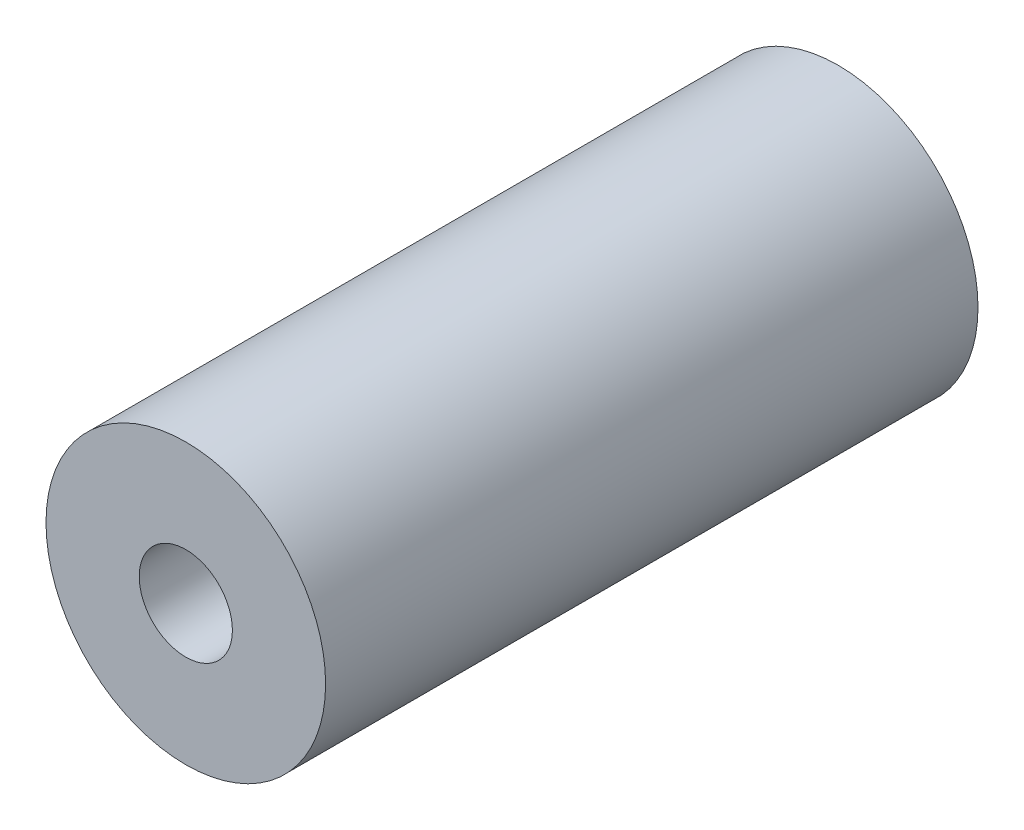
SolidWorks part; units mm, degrees
ref_plane "前视基准面" through (0, 0, 0) normal (0, 0, 1) x (1, 0, 0)
ref_plane "上视基准面" through (0, 0, 0) normal (0, 1, 0) x (1, 0, 0)
ref_plane "右视基准面" through (0, 0, 0) normal (1, 0, 0) x (0, 0, -1)
other "Configuration Table"
sketch "草图1" plane through (0, 0, 0) normal (0, 0, 1) x (1, 0, 0)
  circle A0 centre (0, 0) radius 3
  dimension "D1" = 6
extrude "凸台-拉伸1" add sketch "草图1" along normal blind 14 contours A0
sketch "草图2" plane through (0, 0, 14) normal (0, 0, 1) x (1, 0, 0)
  circle A0 centre (0, 0) radius 1
  dimension "D1" = 2
extrude "切除-拉伸1" cut sketch "草图2" against normal up to next
